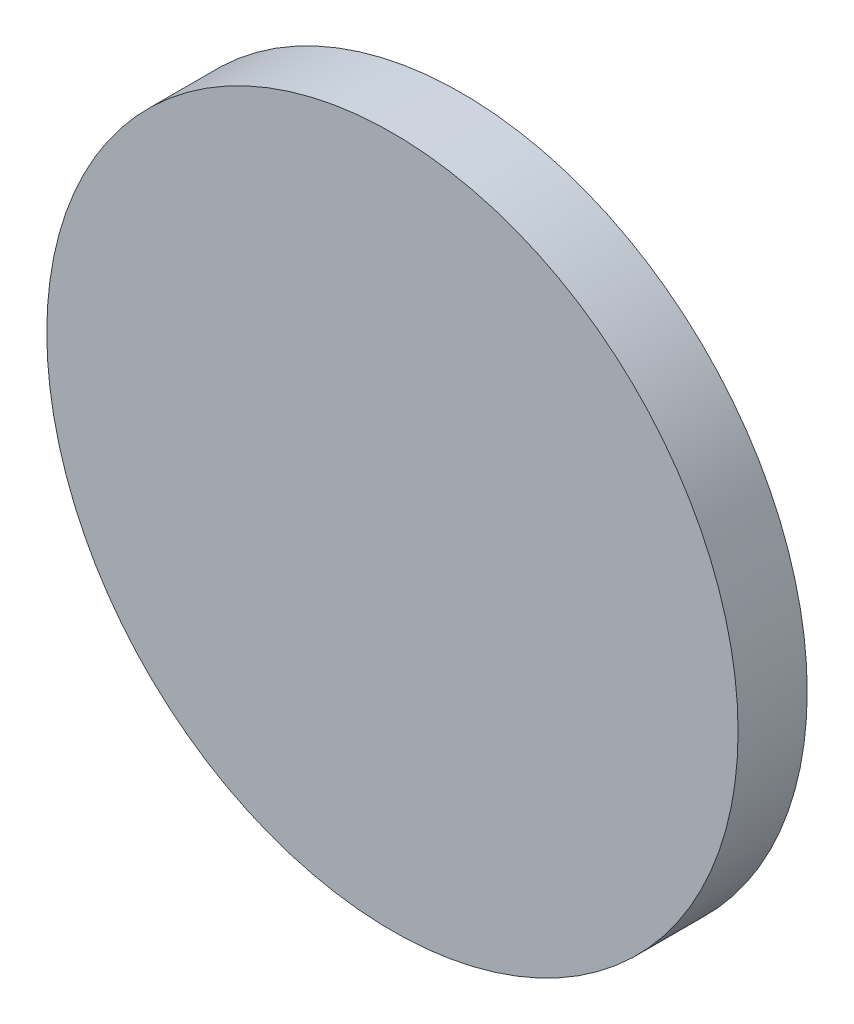
SolidWorks part; units mm, degrees
ref_plane "Plane1" through (0, 0, 0) normal (0, 0, 1) x (1, 0, 0)
ref_plane "Plane2" through (0, 0, 0) normal (0, 1, 0) x (1, 0, 0)
ref_plane "Plane3" through (0, 0, 0) normal (1, 0, 0) x (0, 0, -1)
sketch "s1" plane through (0, 0, 0) normal (0, 0, 1) x (1, 0, 0)
  circle A1 centre (0, 0) radius 10
extrude "1" add sketch "s1" along normal mid plane 2
